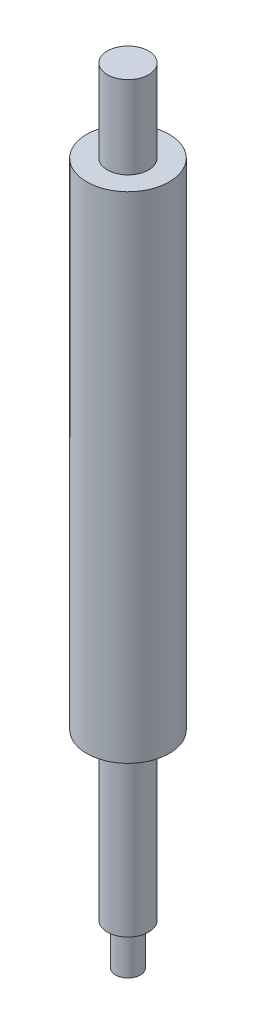
SolidWorks part; units mm, degrees
ref_plane "Plan de face" through (0, 0, 0) normal (0, 0, 1) x (1, 0, 0)
ref_plane "Plan de dessus" through (0, 0, 0) normal (0, 1, 0) x (1, 0, 0)
ref_plane "Plan de droite" through (0, 0, 0) normal (1, 0, 0) x (0, 0, -1)
sketch "Esquisse1" plane through (0, 0, 0) normal (0, 0, 1) x (1, 0, 0)
  line L0 (2.5, 5) -> (1.5, 5)
  line L1 (2.5, 5) -> (2.5, 25)
  line L2 (2.5, 25) -> (5, 25)
  line L3 (5, 25) -> (5, 85)
  line L4 (5, 85) -> (2.5, 85)
  line L5 (2.5, 85) -> (2.5, 95)
  line L6 (2.5, 95) -> (0, 95)
  line L7 (0, 95) -> (0, 0)
  line L8 (1.5, 5) -> (1.5, 0)
  line L9 (1.5, 0) -> (0, 0)
  point P12 (1.5, 2.5)
  dimension "D1" = 2.5
  dimension "D2" = 5
  dimension "D3" = 20
  dimension "D4" = 10
  dimension "D5" = 5
  dimension "D6" = 1.5
  dimension "D7" = 95
revolve "Révolution1" add sketch "Esquisse1" angle 360 about L7
